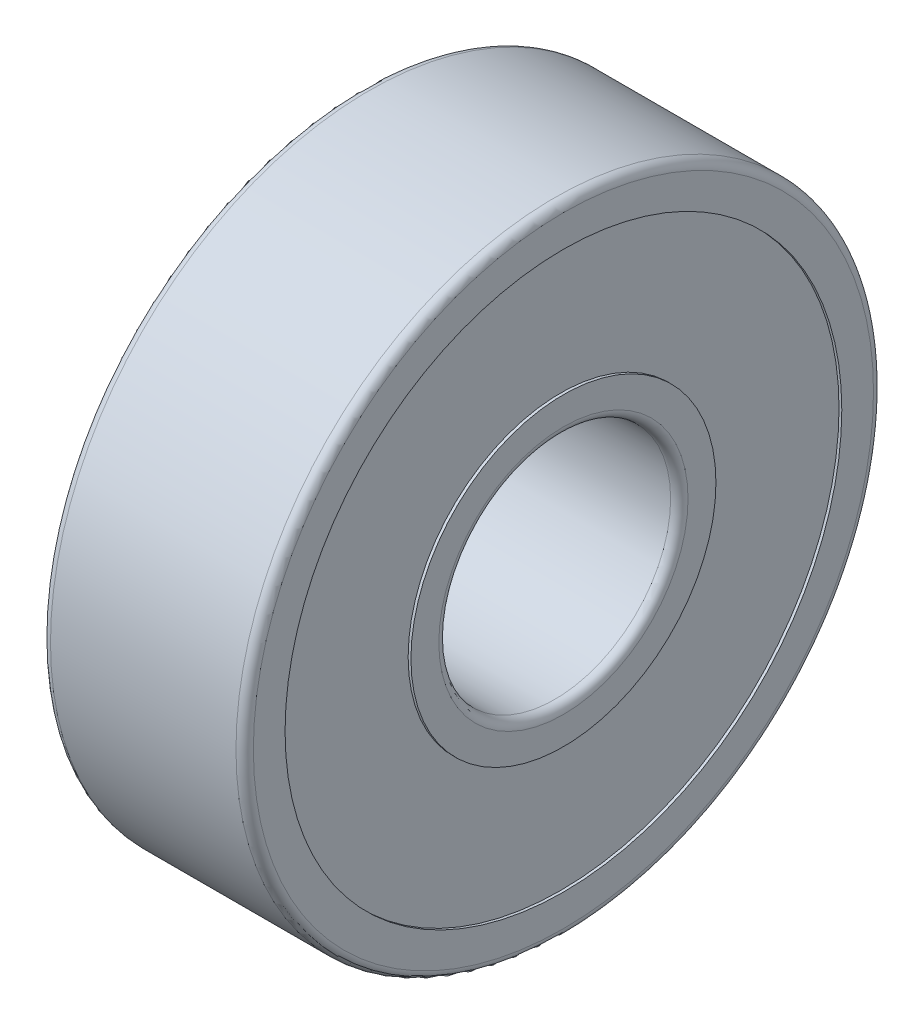
SolidWorks part; units mm, degrees
material "201 Annealed Stainless Steel (SS)"
ref_plane "Front Plane" through (0, 0, 0) normal (0, 0, 1) x (1, 0, 0)
ref_plane "Top Plane" through (0, 0, 0) normal (0, 1, 0) x (1, 0, 0)
ref_plane "Right Plane" through (0, 0, 0) normal (1, 0, 0) x (0, 0, -1)
ref_plane "Plane1" through (0, 0, 0) normal (0, 0, -1) x (-1, 0, 0)
sketch "Sketch1" plane through (0, 0, 0) normal (0, 0, -1) x (-1, 0, 0)
  line L0 (-6.7, 4) -> (-0.3, 4)
  line L1 (0, 4.3) -> (0, 5.2629)
  line L2 (0, 5.2629) -> (-0.0956, 5.2629)
  line L3 (-0.0956, 5.2629) -> (-0.0956, 9.6056)
  line L4 (-0.0956, 9.6056) -> (0, 9.6056)
  line L5 (0, 9.6056) -> (0, 10.7)
  line L6 (-0.3, 11) -> (-6.7, 11)
  line L7 (-7, 10.7) -> (-7, 9.6056)
  line L8 (-7, 9.6056) -> (-6.9044, 9.6056)
  line L9 (-6.9044, 9.6056) -> (-6.9044, 5.2629)
  line L10 (-6.9044, 5.2629) -> (-7, 5.2629)
  line L11 (-7, 5.2629) -> (-7, 4.3)
  line L12 (-7.0035, 0) -> (0.0035, 0) construction
  arc A0 (-7, 4.3) -> (-6.7, 4) centre (-6.7, 4.3) ccw
  arc A1 (-0.3, 4) -> (0, 4.3) centre (-0.3, 4.3) ccw
  arc A2 (0, 10.7) -> (-0.3, 11) centre (-0.3, 10.7) ccw
  arc A3 (-6.7, 11) -> (-7, 10.7) centre (-6.7, 10.7) ccw
revolve "Revolve1" add sketch "Sketch1" angle 360 about L12
